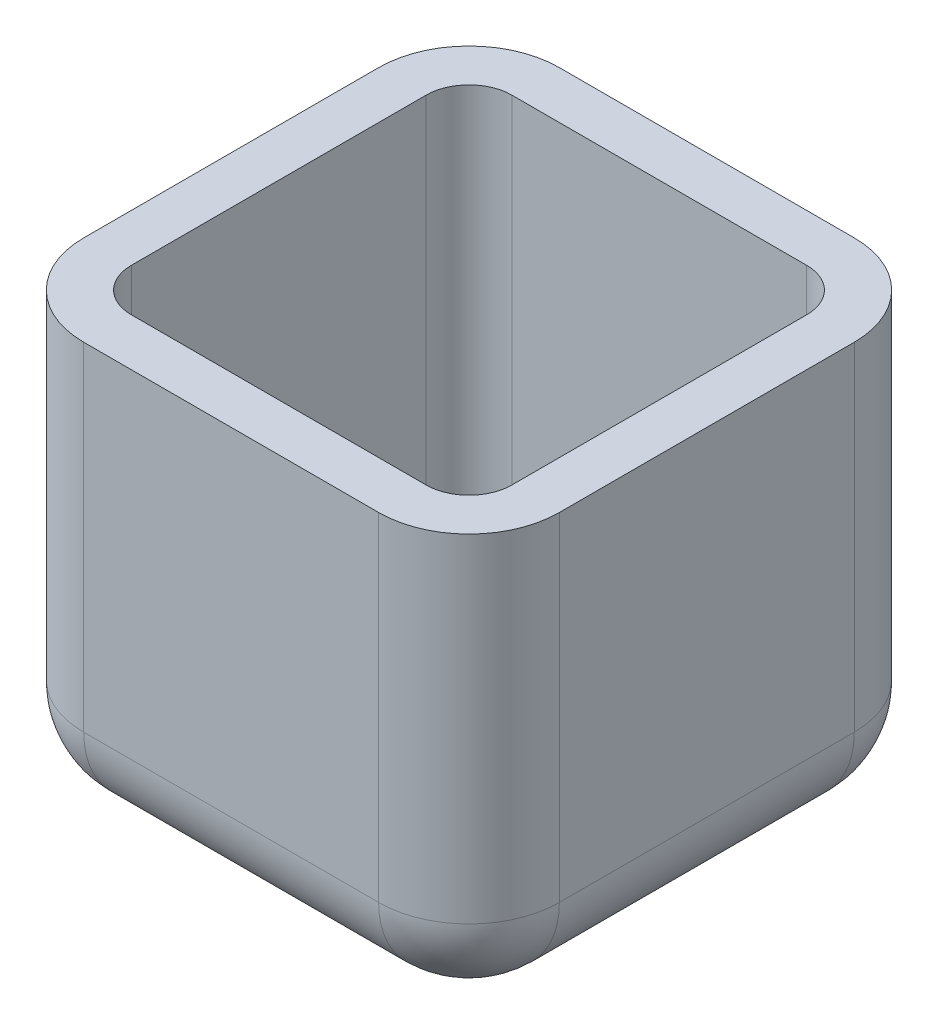
SolidWorks part; units mm, degrees
material "Rubber"
ref_plane "Front Plane" through (0, 0, 0) normal (0, 0, 1) x (1, 0, 0)
ref_plane "Top Plane" through (0, 0, 0) normal (0, 1, 0) x (1, 0, 0)
ref_plane "Right Plane" through (0, 0, 0) normal (1, 0, 0) x (0, 0, -1)
sketch "Sketch1" plane through (0, 0, 0) normal (0, 1, 0) x (1, 0, 0)
  line L1 (-25, 25) -> (25, 25)
  line L2 (-25, 25) -> (-25, -25)
  line L3 (-25, -25) -> (25, -25)
  line L4 (25, 25) -> (25, -25)
  line L5 (-25, 25) -> (25, -25) construction
  line L6 (-25, -25) -> (25, 25) construction
  point P0 (0, 0)
  dimension "D1" = 50
  dimension "D2" = 50
extrude "Boss-Extrude1" add sketch "Sketch1" along normal blind 45
shell "Shell1" thickness 5
fillet "Fillet1" radius 4.5 4 edges at (-20, 25, 20) (20, 25, 20) (20, 25, -20) (-20, 25, -20)
fillet "Fillet2" radius 9.5 8 edges at (0, 0, -25) (-25, 0, 0) (0, 0, 25) (25, 0, 0) (25, 22.5, 25) (-25, 22.5, 25) (-25, 22.5, -25) (25, 22.5, -25)
